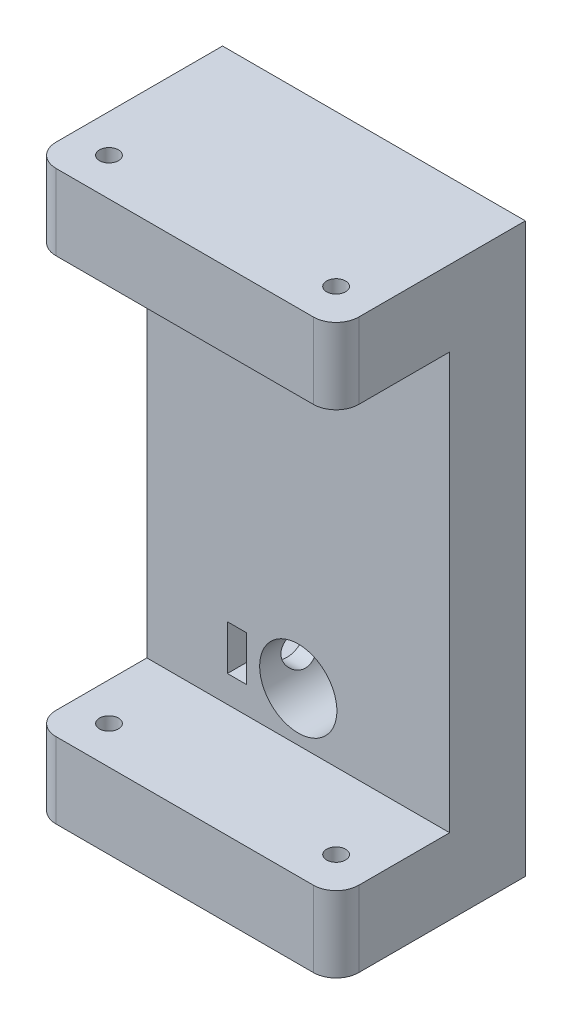
SolidWorks part; units mm, degrees
ref_plane "Front Plane" through (0, 0, 0) normal (0, 0, 1) x (1, 0, 0)
ref_plane "Top Plane" through (0, 0, 0) normal (0, 1, 0) x (1, 0, 0)
ref_plane "Right Plane" through (0, 0, 0) normal (1, 0, 0) x (0, 0, -1)
sketch "Sketch1" plane through (0, 0, 0) normal (0, 0, 1) x (1, 0, 0)
  line L9 (-20, -37.5) -> (20, -37.5)
  line L10 (-20, -37.5) -> (-20, 37.5)
  line L11 (-20, 37.5) -> (20, 37.5)
  line L12 (20, -37.5) -> (20, 37.5)
  point P0 (0, 0)
  dimension "D1" = 75
  dimension "D2" = 40
extrude "Boss-Extrude1" add sketch "Sketch1" along normal blind 10
sketch "Sketch2" plane through (0, 0, 10) normal (0, 0, 1) x (1, 0, 0)
  line L5 (20, -37.5) -> (20, 37.5) construction
  line L6 (-20, 37.5) -> (20, 37.5)
  line L9 (-20, 37.5) -> (-20, 27.5)
  line L10 (-20, 27.5) -> (20, 27.5)
  line L11 (20, 37.5) -> (20, 27.5)
  line L13 (-20, -37.5) -> (20, -37.5)
  line L14 (-20, -37.5) -> (-20, -27.5)
  line L15 (-20, -27.5) -> (20, -27.5)
  line L16 (20, -37.5) -> (20, -27.5)
  point P0 (0, 0)
  dimension "D1" = 10
  dimension "D2" = 10
extrude "Boss-Extrude2" add sketch "Sketch2" along normal blind 15
sketch "Sketch3" plane through (0, 37.5, 0) normal (0, 1, 0) x (1, 0, 0)
  line L0 (-20, -25) -> (-20, 0) construction
  line L1 (20, -25) -> (-20, -25) construction
  circle A0 centre (-15, -20) radius 1.25
  circle A1 centre (15, -20) radius 1.25
  dimension "D1" = 2.5
  dimension "D4" = 5
  dimension "D5" = 30
  dimension "D2" = 5
  dimension "D3" = 5
extrude "Cut-Extrude1" cut sketch "Sketch3" against normal blind 70
fillet "Fillet1" radius 3 2 edges at (-20, 32.5, 25) (20, 32.5, 25)
fillet "Fillet2" radius 3 2 edges at (20, -32.5, 25) (-20, -32.5, 25)
sketch "Sketch4" plane through (0, 0, 0) normal (0, 0, -1) x (-1, 0, 0)
  line L0 (20, -37.5) -> (-20, -37.5) construction
  circle A0 centre (0, -21) radius 5.1
  dimension "D1" = 10.2
  dimension "D2" = 16.5
extrude "Cut-Extrude2" cut sketch "Sketch4" against normal blind 10
sketch "Esquisse1" plane through (-20, 0, 0) normal (-1, 0, 0) x (0, 0, 1)
  line L3 (22, -27.5) -> (10, -27.5) construction
  circle A0 centre (4.6386, -21) radius 2.55
  dimension "D1" = 5.1
  dimension "D2" = 6.5
extrude "Enlèv. mat.-Extru.1" cut sketch "Esquisse1" against normal up to next and the other way through all
sketch "Esquisse2" plane through (0, 0, 0) normal (0, 0, -1) x (-1, 0, 0)
  line L0 (20, -37.5) -> (-20, -37.5) construction
  line L1 (6.8586, -18.0375) -> (9.3586, -18.0375)
  line L2 (6.8586, -18.0375) -> (6.8586, -23.9625)
  line L3 (6.8586, -23.9625) -> (9.3586, -23.9625)
  line L4 (9.3586, -18.0375) -> (9.3586, -23.9625)
  line L5 (6.8586, -18.0375) -> (9.3586, -23.9625) construction
  line L6 (6.8586, -23.9625) -> (9.3586, -18.0375) construction
  point P0 (8.1086, -21)
  dimension "D1" = 2.5
  dimension "D2" = 16.5
extrude "Enlèv. mat.-Extru.2" cut sketch "Esquisse2" against normal through all
